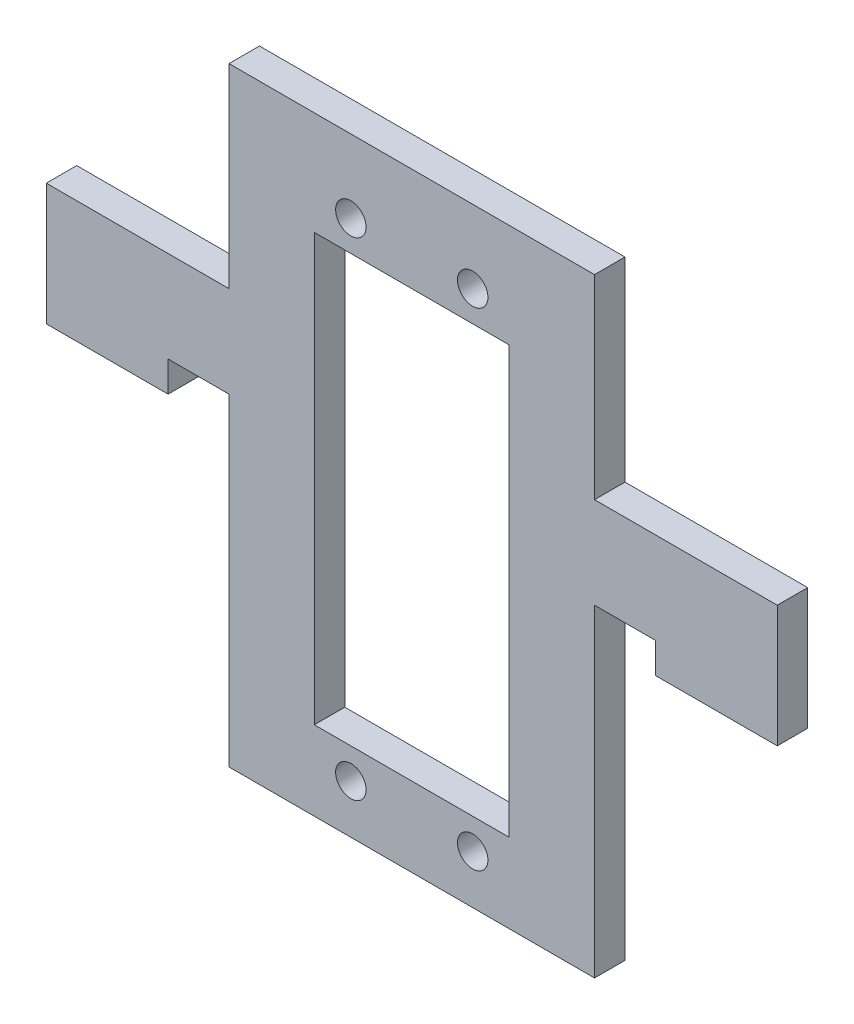
SolidWorks part; units mm, degrees
ref_plane "Front Plane" through (0, 0, 0) normal (0, 0, 1) x (1, 0, 0)
ref_plane "Top Plane" through (0, 0, 0) normal (0, 1, 0) x (1, 0, 0)
ref_plane "Right Plane" through (0, 0, 0) normal (1, 0, 0) x (0, 0, -1)
sketch "Sketch1" plane through (0, 0, 0) normal (0, 0, 1) x (1, 0, 0)
  line L0 (-8.89, 25.4) -> (-15.24, 25.4)
  line L1 (0, 0) -> (20.32, 0)
  line L2 (0, 0) -> (0, 44.45)
  line L3 (0, 44.45) -> (20.32, 44.45)
  line L4 (20.32, 0) -> (20.32, 44.45)
  line L5 (-15.24, 25.4) -> (-15.24, 22.225)
  line L6 (-15.24, 22.225) -> (-27.94, 22.225)
  line L7 (-27.94, 22.225) -> (-27.94, 34.925)
  line L8 (-27.94, 34.925) -> (-8.89, 34.925)
  line L9 (-8.89, 34.925) -> (-8.89, 55.245)
  line L10 (-8.89, 55.245) -> (29.21, 55.245)
  line L11 (29.21, 55.245) -> (29.21, 34.925)
  line L12 (29.21, 34.925) -> (48.26, 34.925)
  line L13 (48.26, 34.925) -> (48.26, 22.225)
  line L14 (48.26, 22.225) -> (35.56, 22.225)
  line L15 (35.56, 22.225) -> (35.56, 25.4)
  line L16 (35.56, 25.4) -> (29.21, 25.4)
  line L17 (29.21, 25.4) -> (29.21, -8.255)
  line L18 (29.21, -8.255) -> (-8.89, -8.255)
  line L19 (-8.89, -8.255) -> (-8.89, 25.4)
  line L20 (0, 22.225) -> (20.32, 22.225) construction
  line L21 (3.81, 47.625) -> (16.51, 47.625) construction
  line L22 (10.16, 47.625) -> (10.16, 44.45) construction
  line L23 (-6.9228, 55.245) -> (-6.9228, -8.255) construction
  line L24 (10.16, 47.625) -> (10.16, 55.245) construction
  circle A0 centre (3.81, 47.625) radius 1.5875
  circle A1 centre (16.51, 47.625) radius 1.5875
  circle A2 centre (16.51, -3.175) radius 1.5875
  circle A3 centre (3.81, -3.175) radius 1.5875
  dimension "D3" = 3.175
  dimension "D1" = 44.45
  dimension "D2" = 20.32
  dimension "D4" = 3.175
  dimension "D5" = 12.7
  dimension "D6" = 6.35
  dimension "D7" = 3.175
  dimension "D8" = 12.7
  dimension "D9" = 12.7
  dimension "D10" = 38.1
  dimension "D11" = 63.5
  dimension "D12" = 7.62
  dimension "D13" = 20.32
extrude "Boss-Extrude1" add sketch "Sketch1" along normal blind 3.175
